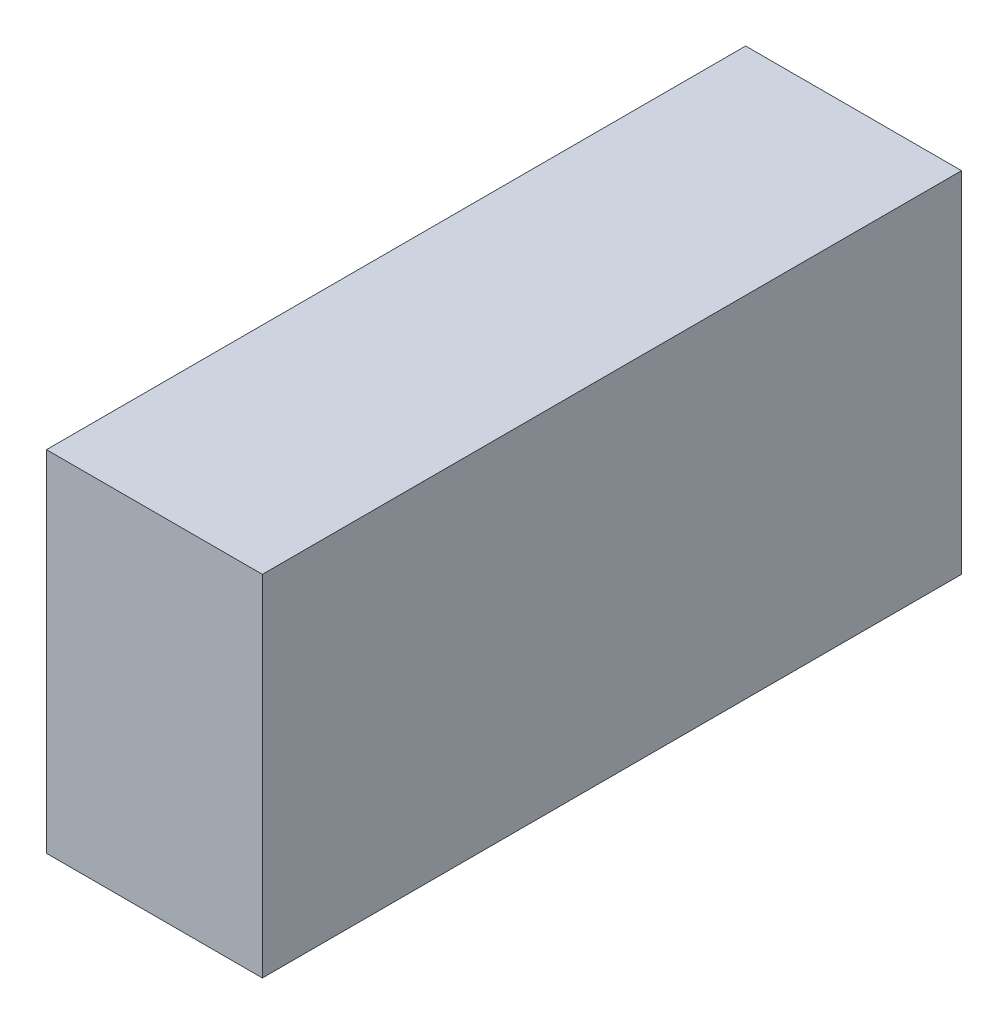
SolidWorks part; units mm, degrees
material "LiPol"
ref_plane "Płaszczyzna przednia" through (0, 0, 0) normal (0, 0, 1) x (1, 0, 0)
ref_plane "Płaszczyzna górna" through (0, 0, 0) normal (0, 1, 0) x (1, 0, 0)
ref_plane "Płaszczyzna prawa" through (0, 0, 0) normal (1, 0, 0) x (0, 0, -1)
sketch "Szkic1" plane through (0, 0, 0) normal (0, 1, 0) x (1, 0, 0)
  line L0 (0, 0) -> (0, 136)
  line L1 (0, 136) -> (42, 136)
  line L2 (42, 136) -> (42, 0)
  line L3 (42, 0) -> (0, 0)
  dimension "D1" = 136
  dimension "D2" = 42
extrude "Dodanie-wyciągnięcie1" add sketch "Szkic1" along normal blind 68
